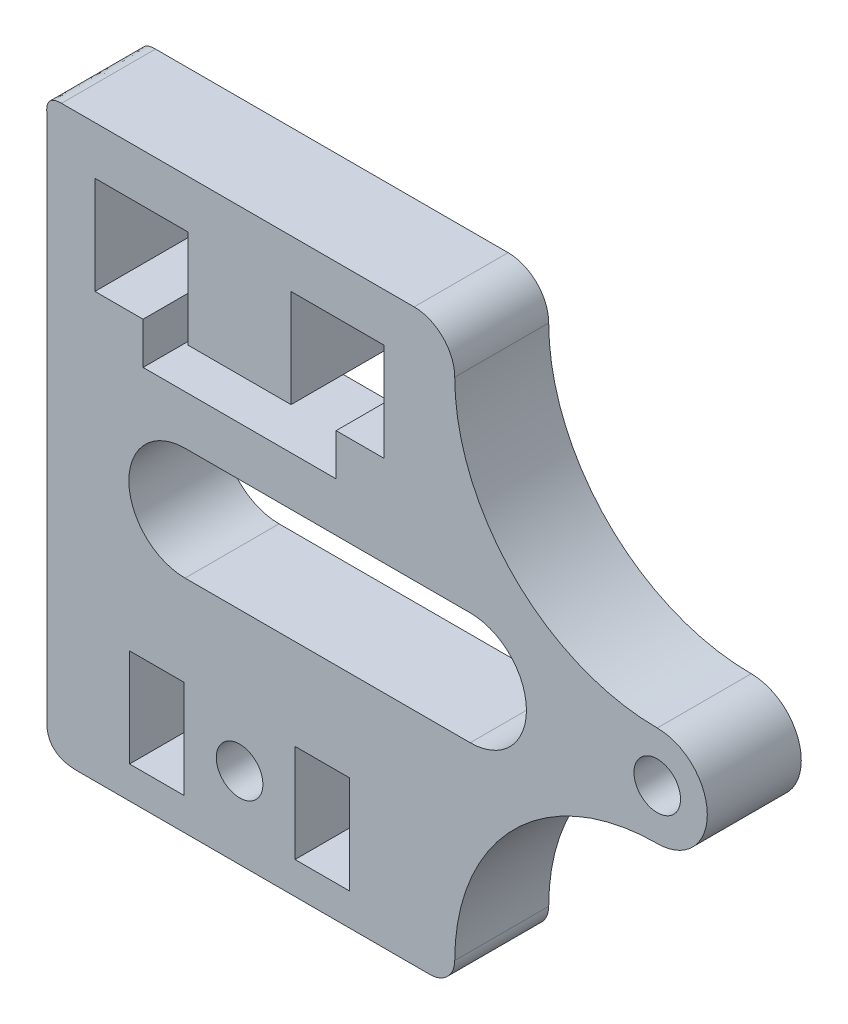
SolidWorks part; units mm, degrees
material "Acrylic (Medium-high impact)"
ref_plane "Front Plane" through (0, 0, 0) normal (0, 0, 1) x (1, 0, 0)
ref_plane "Top Plane" through (0, 0, 0) normal (0, 1, 0) x (1, 0, 0)
ref_plane "Right Plane" through (0, 0, 0) normal (1, 0, 0) x (0, 0, -1)
sketch "Sketch1" plane through (0, 0, 0) normal (0, 0, 1) x (1, 0, 0)
  line L0 (405.5669, 551.1889) -> (405.5669, 553.7889)
  line L1 (396.3551, 553.7889) -> (402.763, 553.7889)
  line L2 (393.5512, 553.7889) -> (393.5512, 551.1889)
  line L3 (393.5512, 551.1889) -> (405.5669, 551.1889)
  line L4 (390.5551, 559.8889) -> (390.5551, 553.7889)
  line L5 (393.5512, 553.7889) -> (390.5551, 553.7889)
  line L6 (396.3551, 559.8889) -> (390.5551, 559.8889)
  line L7 (396.3551, 553.7889) -> (396.3551, 559.8889)
  line L8 (405.5669, 553.7889) -> (408.563, 553.7889)
  line L9 (408.563, 553.7889) -> (408.563, 559.8889)
  line L10 (402.763, 559.8889) -> (402.763, 553.7889)
  line L11 (408.563, 559.8889) -> (402.763, 559.8889)
  line L12 (392.709, 535.4889) -> (392.709, 529.3889)
  line L13 (392.709, 529.3889) -> (396.109, 529.3889)
  line L14 (396.109, 535.4889) -> (392.709, 535.4889)
  line L15 (396.109, 529.3889) -> (396.109, 535.4889)
  line L16 (403.009, 529.3889) -> (406.4091, 529.3889)
  line L17 (406.4091, 529.3889) -> (406.4091, 535.4889)
  line L18 (403.009, 535.4889) -> (403.009, 529.3889)
  line L19 (406.4091, 535.4889) -> (403.009, 535.4889)
  line L20 (388.4729, 562.8889) -> (410.4246, 562.8889)
  line L21 (387.5551, 561.972) -> (387.5551, 529.3047)
  line L22 (389.4729, 527.3889) -> (411.4246, 527.3889)
  line L23 (-605.591, 535.4889) -> (49394.409, 535.4889) construction
  line L24 (396.1657, 548.1389) -> (413.9157, 548.1389)
  line L25 (396.1657, 541.1389) -> (413.9157, 541.1389)
  line L26 (-600.441, 544.6389) -> (49399.559, 544.6389) construction
  line L27 (398.109, 532.4389) -> (396.109, 532.4389) construction
  line L28 (401.009, 532.4389) -> (403.009, 532.4389) construction
  line L29 (399.559, -466.6171) -> (399.559, 49533.3829) construction
  line L30 (425.559, -455.7473) -> (425.559, 49544.2527) construction
  line L31 (-608.8734, 553.7889) -> (49391.1266, 553.7889) construction
  line L32 (421.909, 544.6389) -> (421.909, 535.4889) construction
  line L33 (421.909, 544.6389) -> (421.909, 553.7889) construction
  line L34 (412.9514, 560.3621) -> (412.9514, 528.9157) construction
  circle A0 centre (425.559, 544.6389) radius 1.45
  arc A1 (396.1657, 548.1389) -> (396.1657, 541.1389) centre (396.1657, 544.6389) ccw
  circle A2 centre (399.559, 532.4389) radius 1.45
  arc A3 (412.9514, 528.9157) -> (425.559, 541.5233) centre (425.559, 528.9157) cw
  arc A4 (412.9514, 560.3621) -> (425.559, 547.7545) centre (425.559, 560.3621) ccw
  arc A5 (425.559, 547.7545) -> (425.559, 541.5233) centre (425.559, 544.6389) cw
  arc A7 (413.9157, 548.1389) -> (413.9157, 541.1389) centre (413.9157, 544.6389) cw
  arc A8 (411.4246, 527.3889) -> (412.9514, 528.9157) centre (411.4246, 528.9157) ccw
  arc A9 (410.4246, 562.8889) -> (412.9514, 560.3621) centre (410.4246, 560.3621) cw
  spline S36 degree 2 poles (387.5551, 561.972) (387.5046, 562.8889) (388.4729, 562.8889) knots 0 0 0 1 1 1
  spline S37 degree 2 poles (387.5551, 529.3047) (387.4496, 527.3889) (389.4729, 527.3889) knots 0 0 0 1 1 1
  point P26 (399.559, 544.6389)
  point P30 (399.559, 553.7889)
  point P38 (394.409, 535.4889)
  point P40 (412.9514, 544.6389)
  dimension "D5" = 2.9
  dimension "D12" = 6.1
  dimension "D18" = 6.4078
  dimension "D16" = 3.5
  dimension "D2" = 3.4
  dimension "D3" = 5.8
  dimension "D4" = 2.6
  dimension "D6" = 2
  dimension "D7" = 18.3
  dimension "D8" = 2
  dimension "D9" = 3
  dimension "D10" = 3
  dimension "D11" = 26
  dimension "D13" = 12.0157
  dimension "D14" = 35.5
  dimension "D15" = 31.4465
  dimension "D17" = 17.75
  dimension "D19" = 13.3924
  dimension "D20" = 22.35
  dimension "D21" = 7
extrude "Boss-Extrude2" add sketch "Sketch1" along normal blind 5.85
